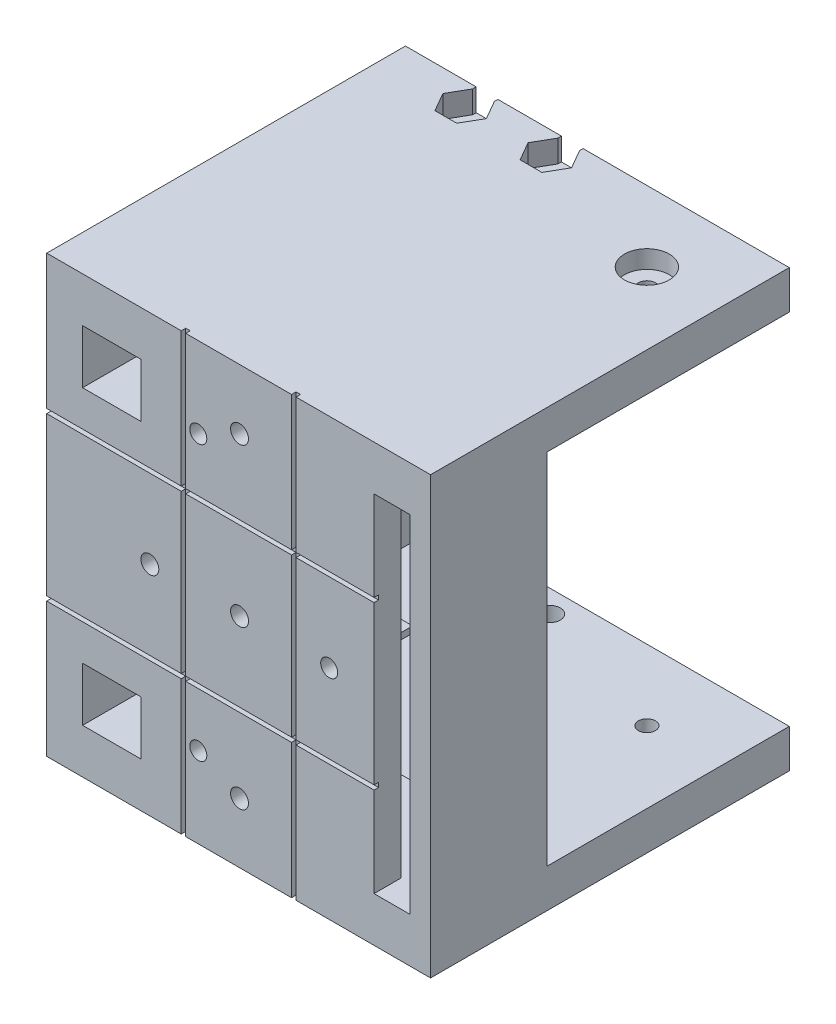
SolidWorks part; units mm, degrees
ref_plane "前视基准面" through (0, 0, 0) normal (0, 0, 1) x (1, 0, 0)
ref_plane "上视基准面" through (0, 0, 0) normal (0, 1, 0) x (1, 0, 0)
ref_plane "右视基准面" through (0, 0, 0) normal (1, 0, 0) x (0, 0, -1)
other "Configuration Table"
sketch "草图1" plane through (0, 0, 0) normal (0, 0, 1) x (1, 0, 0)
  line L3 (4, 5) -> (10.5, 5)
  line L4 (10.5, 5) -> (10.5, 8)
  line L5 (10.5, 8) -> (14.5, 8)
  line L6 (14.5, 8) -> (14.5, 5)
  line L7 (14.5, 5) -> (42.8, 5)
  line L8 (42.8, 5) -> (42.8, 0)
  line L9 (42.8, 0) -> (0, 0)
  line L12 (0, 0) -> (0, 48.6)
  line L13 (0, 48.6) -> (42.8, 48.6)
  line L14 (42.8, 48.6) -> (42.8, 43.6)
  line L15 (42.8, 43.6) -> (14.5, 43.6)
  line L16 (14.5, 43.6) -> (14.5, 40.6)
  line L17 (14.5, 40.6) -> (10.5, 40.6)
  line L18 (10.5, 40.6) -> (10.5, 43.6)
  line L19 (10.5, 43.6) -> (4, 43.6)
  line L20 (4, 43.6) -> (4, 5)
  dimension "D1" = 5
  dimension "D2" = 42.8
  dimension "D3" = 28.3
  dimension "D4" = 4
  dimension "D5" = 6.5
  dimension "D6" = 8
  dimension "D7" = 8
  dimension "D8" = 48.6
  dimension "D9" = 5
  dimension "D10" = 4
extrude "凸台-拉伸1" add sketch "草图1" along normal mid plane 40
sketch "草图2" plane through (0, 0, -20) normal (0, 0, -1) x (-1, 0, 0)
  line L1 (-14.5, 43.6) -> (-10.5, 43.6)
  line L2 (-14.5, 43.6) -> (-14.5, 5)
  line L3 (-14.5, 5) -> (-10.5, 5)
  line L4 (-10.5, 43.6) -> (-10.5, 5)
extrude "切除-拉伸1" cut sketch "草图2" against normal blind 20
sketch "草图3" plane through (0, 43.6, 0) normal (0, -1, 0) x (1, 0, 0)
  line L0 (4, -20) -> (50004, -20) construction
  line L2 (4, -20) -> (4, 49980) construction
  line L3 (9.1, 3.7099) -> (9.1, -49996.2901) construction
  line L4 (18.6, 6.381) -> (18.6, -49993.619) construction
  line L5 (2.1679, -17.5) -> (50002.1679, -17.5) construction
  circle A0 centre (9.1, -17.5) radius 1.175
  circle A1 centre (18.6, -17.5) radius 1.175
  dimension "D4" = 2.35
  dimension "D5" = 2.35
  dimension "D1" = 2.5
  dimension "D2" = 5.1
  dimension "D3" = 9.5
extrude "切除-拉伸2" cut sketch "草图3" against normal through all and the other way through all
sketch "草图4" plane through (0, 0, 20) normal (0, 0, 1) x (1, 0, 0)
  line L0 (10.5, 40.6) -> (10.5, 37.6)
  line L1 (10.5, 37.6) -> (4, 37.6)
  line L2 (4, 5) -> (4, 43.6) construction
  line L3 (4, 37.6) -> (4, 11)
  line L4 (4, 11) -> (10.5, 11)
  line L5 (10.5, 11) -> (10.5, 8)
  line L7 (26.5, 5) -> (26.5, 43.6)
  line L9 (4, 43.6) -> (10.5, 43.6) construction
  line L10 (10.5, 5) -> (4, 5) construction
  line L11 (10.5, 40.6) -> (14.5, 40.6)
  line L12 (14.5, 40.6) -> (14.5, 43.6)
  line L13 (14.5, 43.6) -> (26.5, 43.6)
  line L14 (14.5, 43.6) -> (42.8, 43.6) construction
  line L15 (42.8, 5) -> (14.5, 5) construction
  line L16 (10.5, 8) -> (14.5, 8)
  line L17 (14.5, 8) -> (10.5, 8) construction
  line L18 (14.5, 8) -> (14.5, 5)
  line L19 (14.5, 5) -> (26.5, 5)
  dimension "D1" = 6
  dimension "D2" = 6
  dimension "D3" = 22.5
extrude "凸台-拉伸2" add sketch "草图4" against normal blind 20 contours L7 L13 L12 L11 L0 L1 L3 L4 L5 L16 L18 L19
sketch "草图6" plane through (0, 0, 0) normal (0, 0, -1) x (-1, 0, 0)
  line L0 (-26.5, 43.6) -> (-13.5, 43.6)
  line L1 (-26.5, 5) -> (-26.5, 43.6) construction
  line L2 (-13.5, 43.6) -> (-13.5, 34.6)
  line L3 (-13.5, 34.6) -> (-4, 34.6)
  line L4 (-4, 5) -> (-4, 43.6) construction
  line L5 (-4, 34.6) -> (-4, 14)
  line L6 (-4, 14) -> (-13.5, 14)
  line L7 (-13.5, 14) -> (-13.5, 5)
  line L8 (-26.5, 5) -> (-10.5, 5) construction
  line L9 (-13.5, 5) -> (-26.5, 5)
  line L10 (-42.8, 5) -> (-4, 5) construction
  line L11 (-26.5, 5) -> (-26.5, 43.6)
  line L12 (-4, 43.6) -> (-42.8, 43.6) construction
  line L13 (-10.5, 37.6) -> (-4, 37.6) construction
  line L14 (-10.5, 37.6) -> (-10.5, 43.6) construction
  line L15 (-4, 11) -> (-10.5, 11) construction
  line L16 (-10.5, 5) -> (-10.5, 11) construction
  dimension "D1" = 3
  dimension "D2" = 3
  dimension "D3" = 3
  dimension "D4" = 3
extrude "切除-拉伸3" cut sketch "草图6" against normal blind 17
sketch "草图7" plane through (0, 0, 17) normal (0, 0, -1) x (-1, 0, 0)
  line L0 (-26.5, 24.3) -> (-50026.5, 24.3) construction
  line L1 (-26.5, 43.6) -> (-26.5, 5) construction
  line L2 (-33.3088, 6.7) -> (49966.6912, 6.7) construction
  line L3 (-36.8703, 41.9) -> (49963.1297, 41.9) construction
  circle A0 centre (-21.5, 24.3) radius 1
  circle A1 centre (-11.5, 24.3) radius 1
  circle A2 centre (-21.5, 6.7) radius 1
  circle A3 centre (-21.5, 41.9) radius 1
  point P4 (-26.5, 24.3)
  dimension "D1" = 2
  dimension "D2" = 2
  dimension "D3" = 2
  dimension "D9" = 2
  dimension "D4" = 5
  dimension "D5" = 15
  dimension "D6" = 5
  dimension "D7" = 17.6
  dimension "D8" = 17.6
  dimension "D10" = 5
extrude "切除-拉伸4" cut sketch "草图7" against normal blind 4.8
sketch "草图8" plane through (0, 0, -20) normal (0, 0, -1) x (-1, 0, 0)
  line L0 (0, 48.6) -> (0, 0) construction
  line L1 (-4, 34.6) -> (0, 34.6)
  line L2 (-4, 34.6) -> (-4, 14)
  line L3 (-4, 14) -> (0, 14)
  line L4 (0, 34.6) -> (0, 14)
  line L5 (-13.5, 14) -> (-4, 14) construction
extrude "切除-拉伸5" cut sketch "草图8" against normal blind 25.4
sketch "草图9" plane through (0, 0, 17) normal (0, 0, -1) x (-1, 0, 0)
  circle A0 centre (-21.5, 41.9) radius 1
  circle A1 centre (-21.5, 41.9) radius 1.9
  circle A4 centre (-11.5, 24.3) radius 1
  circle A5 centre (-11.5, 24.3) radius 1.9
  circle A6 centre (-21.5, 6.7) radius 1
  circle A7 centre (-21.5, 6.7) radius 1.9
  dimension "D1" = 2
  dimension "D2" = 2
  dimension "D3" = 2
  dimension "D4" = 3.8
  dimension "D5" = 3.8
  dimension "D6" = 3.8
extrude "凸台-拉伸3" add sketch "草图9" along normal blind 10
sketch "草图10" plane through (0, 48.6, 0) normal (0, 1, 0) x (1, 0, 0)
  line L1 (11.5249, 17.5) -> (10.3124, 19.6)
  line L3 (7.8876, 19.6) -> (6.6751, 17.5)
  line L4 (6.6751, 17.5) -> (7.8876, 15.4)
  line L5 (7.8876, 15.4) -> (10.3124, 15.4)
  line L6 (10.3124, 15.4) -> (11.5249, 17.5)
  line L7 (21.0249, 17.5) -> (19.8124, 19.6)
  line L9 (17.3876, 19.6) -> (16.1751, 17.5)
  line L10 (16.1751, 17.5) -> (17.3876, 15.4)
  line L11 (17.3876, 15.4) -> (19.8124, 15.4)
  line L12 (19.8124, 15.4) -> (21.0249, 17.5)
  line L13 (7.8876, 19.6) -> (7.8876, 20)
  line L14 (42.8, 20) -> (0, 20) construction
  line L15 (7.8876, 20) -> (10.3124, 20)
  line L16 (10.3124, 20) -> (10.3124, 19.6)
  line L17 (17.3876, 19.6) -> (17.3876, 20)
  line L18 (17.3876, 20) -> (19.8124, 20)
  line L19 (19.8124, 20) -> (19.8124, 19.6)
  line L21 (10.3124, 19.6) -> (7.8876, 19.6) [skipped]
  line L22 (18.6, 19.6) -> (17.3876, 19.6) [skipped]
  circle A0 centre (9.1, 17.5) radius 2.5 construction
  circle A1 centre (18.6, 17.5) radius 2.1 construction
extrude "切除-拉伸6" cut sketch "草图10" against normal blind 2.5
sketch "草图11" plane through (0, 0, 0) normal (0, -1, 0) x (1, 0, 0)
  line L1 (11.5249, -17.5) -> (10.3124, -15.4)
  line L2 (10.3124, -15.4) -> (7.8876, -15.4)
  line L3 (7.8876, -15.4) -> (6.6751, -17.5)
  line L4 (6.6751, -17.5) -> (7.8876, -19.6)
  line L6 (10.3124, -19.6) -> (11.5249, -17.5)
  line L7 (21.0249, -17.5) -> (19.8124, -15.4)
  line L8 (19.8124, -15.4) -> (17.3876, -15.4)
  line L9 (17.3876, -15.4) -> (16.1751, -17.5)
  line L10 (16.1751, -17.5) -> (17.3876, -19.6)
  line L12 (19.8124, -19.6) -> (21.0249, -17.5)
  line L13 (7.8876, -19.6) -> (7.8876, -20)
  line L14 (7.8876, -20) -> (10.3124, -20)
  line L15 (10.3124, -20) -> (10.3124, -19.6)
  line L16 (17.3876, -19.6) -> (17.3876, -20)
  line L17 (0, -20) -> (42.8, -20) construction
  line L18 (17.3876, -20) -> (19.8124, -20)
  line L19 (19.8124, -20) -> (19.8124, -19.6)
  line L21 (7.8876, -19.6) -> (9.1, -19.6) [skipped]
  line L22 (18.6, -19.6) -> (19.8124, -19.6) [skipped]
  circle A0 centre (9.1, -17.5) radius 2.1 construction
  circle A1 centre (18.6, -17.5) radius 2.1 construction
extrude "切除-拉伸7" cut sketch "草图11" against normal blind 2.5
sketch "草图14" plane through (0, 0, -20) normal (0, 0, -1) x (-1, 0, 0)
  line L0 (-42.8, 4.3) -> (-12.8, 4.3)
  line L1 (-42.8, 0) -> (-42.8, 5) construction
  line L3 (-12.8, 13.3) -> (-4, 13.3)
  line L5 (-4, 37.6) -> (-4, 34.6) construction
  line L6 (-4, 34.6) -> (-4, 43.6) construction
  line L7 (-4, 35.3) -> (-12.8, 35.3)
  line L9 (-12.8, 44.3) -> (-42.8, 44.3)
  line L10 (-42.8, 43.6) -> (-42.8, 48.6) construction
  line L11 (-42.8, 44.3) -> (-42.8, 43.6)
  line L12 (-42.8, 43.6) -> (-13.5, 43.6)
  line L14 (-13.5, 34.6) -> (-4, 34.6)
  line L15 (-4, 34.6) -> (-13.5, 34.6) construction
  line L16 (-4, 34.6) -> (-13.5, 34.6) construction
  line L17 (-4, 35.3) -> (-4, 34.6)
  line L23 (-13.5, 5) -> (-42.8, 5)
  line L24 (-42.8, 5) -> (-4, 5) construction
  line L25 (-42.8, 5) -> (-42.8, 4.3)
  line L27 (-12.8, 4.3) -> (-12.8, 13.3)
  line L28 (-12.8, 35.3) -> (-12.8, 44.3)
  line L29 (-13.5, 43.6) -> (-13.5, 34.6)
  line L30 (-4, 13.3) -> (-4, 14)
  line L32 (-4, 14) -> (-13.5, 14)
  line L34 (-13.5, 14) -> (-13.5, 5)
  line L35 (-13.5, 14) -> (-4, 14) construction
  line L36 (-4, 14) -> (-4, 11) construction
  dimension "D1" = 0.7
  dimension "D2" = 0.7
  dimension "D3" = 0.7
  dimension "D4" = 0.7
  dimension "D5" = 0.7
  dimension "D6" = 0.7
extrude "切除-拉伸10" cut sketch "草图14" against normal blind 27
sketch "草图15" plane through (0, 0, 0) normal (0, -1, 0) x (1, 0, 0)
  line L0 (34.8, -9.5263) -> (34.8, -50009.5263) construction
  line L1 (40.6603, -12) -> (-49959.3397, -12) construction
  line L2 (42.8, 20) -> (42.8, -20) construction
  line L3 (19.8124, -20) -> (42.8, -20) construction
  circle A0 centre (34.8, -12.1221) radius 0.95
  dimension "D3" = 1.9
  dimension "D1" = 8
  dimension "D2" = 8
extrude "切除-拉伸11" cut sketch "草图15" against normal blind 50
sketch "草图16" plane through (0, 0, 0) normal (0, -1, 0) x (1, 0, 0)
  circle A0 centre (34.8, -12.1221) radius 2.5
  dimension "D1" = 5
extrude "切除-拉伸12" cut sketch "草图16" against normal blind 2
sketch "草图17" plane through (0, 48.6, 0) normal (0, 1, 0) x (1, 0, 0)
  circle A0 centre (34.8, 12.1221) radius 2.5
  dimension "D1" = 5
extrude "切除-拉伸13" cut sketch "草图17" against normal blind 2
sketch "草图18" plane through (26.5, 0, 0) normal (1, 0, 0) x (0, 0, -1)
  line L1 (-17, 43.6) -> (-20, 43.6)
  line L2 (-17, 43.6) -> (-17, 5)
  line L3 (-17, 5) -> (-20, 5)
  line L4 (-20, 43.6) -> (-20, 5)
extrude "凸台-拉伸4" add sketch "草图18" along normal blind 10
sketch "草图19" plane through (0, 0, 20) normal (0, 0, 1) x (1, 0, 0)
  line L0 (42.8, 48.6) -> (0, 48.6) construction
  line L1 (15, 48.6) -> (15.5, 48.6)
  line L2 (15, 48.6) -> (15, 33.6)
  line L3 (15, 0) -> (15.5, 0)
  line L4 (15.5, 48.6) -> (15.5, 33.6)
  line L5 (0, 0) -> (42.8, 0) construction
  line L6 (0, 48.6) -> (0, 0) construction
  line L7 (27.3, 48.6) -> (27.8, 48.6)
  line L8 (27.3, 48.6) -> (27.3, 33.6)
  line L9 (27.3, 0) -> (27.8, 0)
  line L10 (27.8, 48.6) -> (27.8, 33.6)
  line L11 (0, 15) -> (15, 15)
  line L12 (0, 15) -> (0, 15.5)
  line L13 (0, 15.5) -> (15, 15.5)
  line L14 (36.5, 15) -> (36.5, 15.5)
  line L15 (36.5, 43.6) -> (36.5, 5) construction
  line L16 (42.8, 0) -> (42.8, 5) construction
  line L17 (36.5, 33.1) -> (27.8, 33.1)
  line L18 (36.5, 33.1) -> (36.5, 33.6)
  line L19 (36.5, 33.6) -> (27.8, 33.6)
  line L20 (0, 33.1) -> (0, 33.6)
  line L21 (15.5, 15) -> (27.3, 15)
  line L22 (15.5, 15) -> (15.5, 0)
  line L23 (15.5, 15.5) -> (27.3, 15.5)
  line L24 (15, 15) -> (15, 0)
  line L25 (27.8, 15) -> (36.5, 15)
  line L26 (27.8, 15) -> (27.8, 0)
  line L27 (27.8, 15.5) -> (36.5, 15.5)
  line L28 (27.3, 15) -> (27.3, 0)
  line L29 (15, 33.1) -> (15, 15.5)
  line L30 (15, 33.1) -> (0, 33.1)
  line L31 (15.5, 33.1) -> (15.5, 15.5)
  line L32 (15, 33.6) -> (0, 33.6)
  line L33 (27.3, 33.6) -> (15.5, 33.6)
  line L34 (27.3, 33.1) -> (27.3, 15.5)
  line L35 (27.3, 33.1) -> (15.5, 33.1)
  line L36 (27.8, 33.1) -> (27.8, 15.5)
  dimension "D1" = 0.5
  dimension "D2" = 0.5
  dimension "D3" = 15
  dimension "D4" = 15
  dimension "D5" = 0.5
  dimension "D6" = 15
  dimension "D7" = 0.5
  dimension "D8" = 15
extrude "切除-拉伸14" cut sketch "草图19" against normal blind 0.5
sketch "草图20" plane through (0, 0, 17) normal (0, 0, -1) x (-1, 0, 0)
  line L0 (-21.5, 24.3) -> (-50021.5, 24.3) construction
  line L1 (-36.5, 5) -> (-36.5, 43.6) construction
  circle A0 centre (-31.5, 24.3) radius 0.95
  dimension "D1" = 1.9
  dimension "D2" = 5
extrude "切除-拉伸15" cut sketch "草图20" against normal blind 10.5
sketch "草图21" plane through (0, 0, -20) normal (0, 0, -1) x (-1, 0, 0)
  line L1 (-12.8, 44.3) -> (-4, 44.3)
  line L2 (-12.8, 44.3) -> (-12.8, 43.6)
  line L3 (-12.8, 43.6) -> (-4, 43.6)
  line L4 (-4, 44.3) -> (-4, 43.6)
  line L5 (-12.8, 4.3) -> (-4, 4.3)
  line L6 (-12.8, 4.3) -> (-12.8, 5)
  line L7 (-12.8, 5) -> (-4, 5)
  line L8 (-4, 4.3) -> (-4, 5)
extrude "切除-拉伸16" cut sketch "草图21" against normal blind 12
sketch "草图23" plane through (0, 0, 20) normal (0, 0, 1) x (1, 0, 0)
  line L0 (27.8, 0) -> (42.8, 0) construction
  line L1 (42.8, 48.6) -> (40.5, 48.6)
  line L2 (42.8, 48.6) -> (42.8, 0)
  line L3 (42.8, 0) -> (40.5, 0)
  line L4 (40.5, 48.6) -> (40.5, 0)
  line L5 (36.5, 33.1) -> (36.5, 15.5) construction
  dimension "D1" = 4
extrude "凸台-拉伸5" add sketch "草图23" against normal blind 13
sketch "草图26" plane through (0, 0, 20) normal (0, 0, 1) x (1, 0, 0)
  line L0 (0, 15) -> (0, 0) construction
  line L1 (15.5, 0) -> (27.3, 0) construction
  line L2 (0, 48.6) -> (0, 33.6) construction
  line L3 (27.3, 48.6) -> (15.5, 48.6) construction
  circle A0 centre (16.9, 9) radius 0.95
  circle A1 centre (16.9, 39.6) radius 0.95
  dimension "D5" = 1.9
  dimension "D6" = 1.9
  dimension "D1" = 16.9
  dimension "D2" = 9
  dimension "D3" = 16.9
  dimension "D4" = 9
extrude "切除-拉伸17" cut sketch "草图26" against normal blind 10
sketch "草图27" plane through (0, 0, 7) normal (0, 0, -1) x (-1, 0, 0)
  circle A0 centre (-21.5, 41.9) radius 1.25
  circle A1 centre (-11.5, 24.3) radius 1.25
  circle A2 centre (-21.5, 6.7) radius 1.25
  dimension "D1" = 2.5
  dimension "D2" = 2.5
  dimension "D3" = 2.5
extrude "切除-拉伸18" cut sketch "草图27" against normal blind 2
